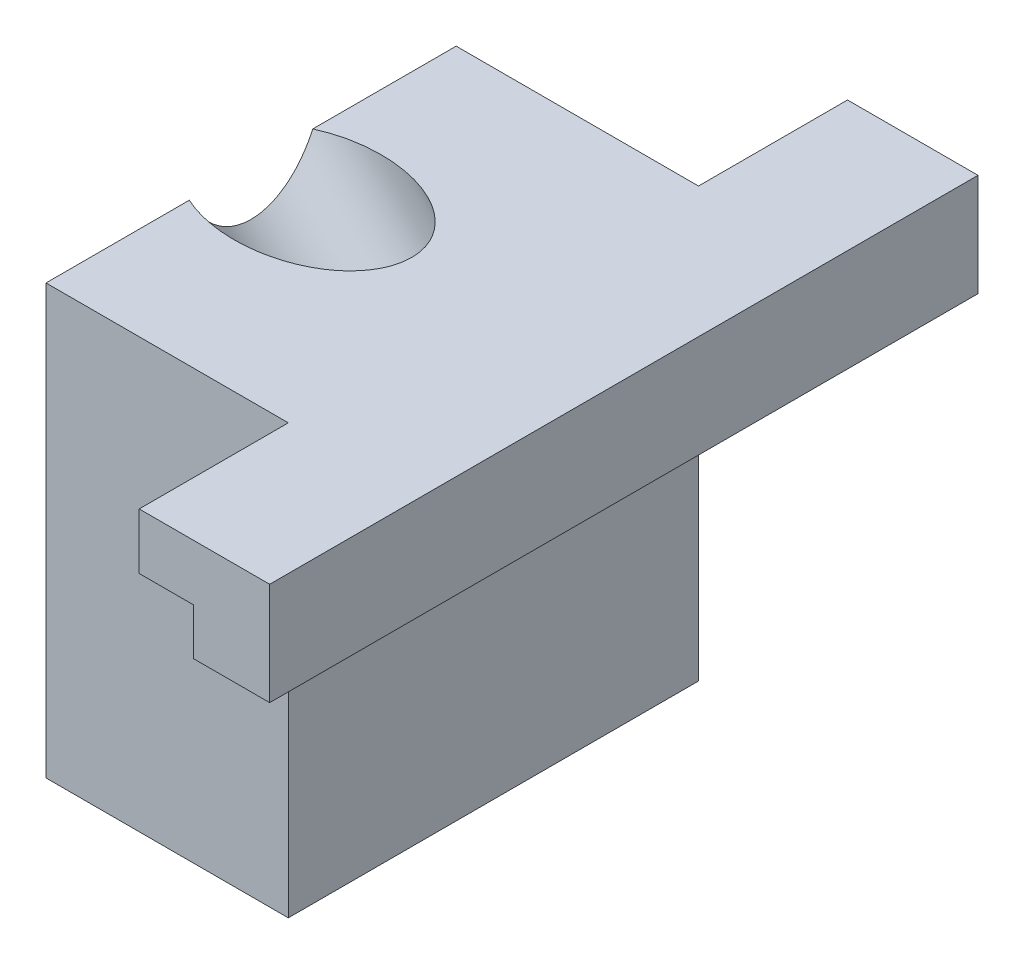
SolidWorks part; units mm, degrees
ref_plane "前视基准面" through (0, 0, 0) normal (0, 0, 1) x (1, 0, 0)
ref_plane "上视基准面" through (0, 0, 0) normal (0, 1, 0) x (1, 0, 0)
ref_plane "右视基准面" through (0, 0, 0) normal (1, 0, 0) x (0, 0, -1)
sketch "草图1" plane through (0, 0, 0) normal (1, 0, 0) x (0, 0, -1)
  line L1 (-11, 10) -> (11, 10)
  line L2 (-11, 10) -> (-11, -10)
  line L3 (-11, -10) -> (11, -10)
  line L4 (11, 10) -> (11, -10)
  line L5 (-11, 10) -> (11, -10) construction
  line L6 (-11, -10) -> (11, 10) construction
  point P0 (0, 0)
  dimension "D1" = 20
  dimension "D2" = 22
extrude "凸台-拉伸1" add sketch "草图1" along normal blind 13
sketch "草图2" plane through (0, 10, 0) normal (0, 1, 0) x (1, 0, 0)
  line L0 (13, 11) -> (13, -11) construction
  line L1 (0, -11) -> (15.9, -11)
  line L2 (0, -11) -> (0, 11.0046)
  line L3 (0, 11.0046) -> (15.9, 11.0046)
  line L4 (15.9, -11) -> (15.9, 11.0046)
  dimension "D1" = 2.9
extrude "凸台-拉伸2" add sketch "草图2" along normal blind 3
sketch "草图3" plane through (15.9, 0, 0) normal (1, 0, 0) x (0, 0, -1)
  line L0 (11, -10) -> (11, 10) construction
  line L1 (-11, 13) -> (11, 13)
  line L2 (-11, 13) -> (-11, 7.5)
  line L3 (-11, 7.5) -> (11, 7.5)
  line L4 (11, 13) -> (11, 7.5)
  line L5 (11, 10) -> (-11, 10) construction
  dimension "D1" = 2.5
extrude "凸台-拉伸3" add sketch "草图3" along normal blind 4.1
sketch "草图5" plane through (0, 0, 11) normal (0, 0, 1) x (1, 0, 0)
  line L0 (0, 13) -> (20, 13) construction
  line L1 (13, 13) -> (13, 10)
  line L2 (20, 7.5) -> (20, 13)
  line L3 (20, 13) -> (13, 13)
  line L4 (13, 10) -> (15.9, 10)
  line L5 (15.9, 10) -> (15.9, 7.5)
  line L6 (15.9, 7.5) -> (20, 7.5)
  point P7 (13, 10)
  point P8 (15.9, 7.5)
extrude "凸台-拉伸4" add sketch "草图5" along normal blind 8
sketch "草图6" plane through (0, 0, -11) normal (0, 0, -1) x (-1, 0, 0)
  line L0 (-13, 13) -> (-13, 10)
  line L1 (-13, 10) -> (-15.9, 10)
  line L2 (-20, 7.5) -> (-20, 13)
  line L3 (-20, 13) -> (-13, 13)
  line L4 (-15.9, 10) -> (-15.9, 7.5)
  line L5 (-15.9, 7.5) -> (-20, 7.5)
extrude "凸台-拉伸5" add sketch "草图6" along normal blind 8
sketch "草图7" plane through (13, 0, 0) normal (1, 0, 0) x (0, 0, -1)
  line L0 (11, 10) -> (-11, 10) construction
  circle A0 centre (0, 2.1) radius 1.5
  dimension "D1" = 3
  dimension "D2" = 7.9
extrude "切除-拉伸1" cut sketch "草图7" against normal blind 5
sketch "草图8" plane through (0, 13, 0) normal (0, 1, 0) x (1, 0, 0)
  line L0 (3, -11) -> (3, 11.0046)
  line L1 (0, -11) -> (13, -11) construction
  line L2 (13, 11.0046) -> (0, 11.0046) construction
  line L3 (0, 11.0046) -> (0, -11) construction
  dimension "D1" = 3
ref_plane "基准面1" through (-5, 5, 0) normal (-0.7071, 0.7071, 0) x (0, 0, -1)
sketch "草图9" plane through (-5, 5, 0) normal (-0.7071, 0.7071, 0) x (0, 0, -1)
  circle A0 centre (0, -11.3416) radius 3.95
  dimension "D1" = 7.9
extrude "切除-拉伸2" cut sketch "草图9" against normal blind 9 and the other way through all
